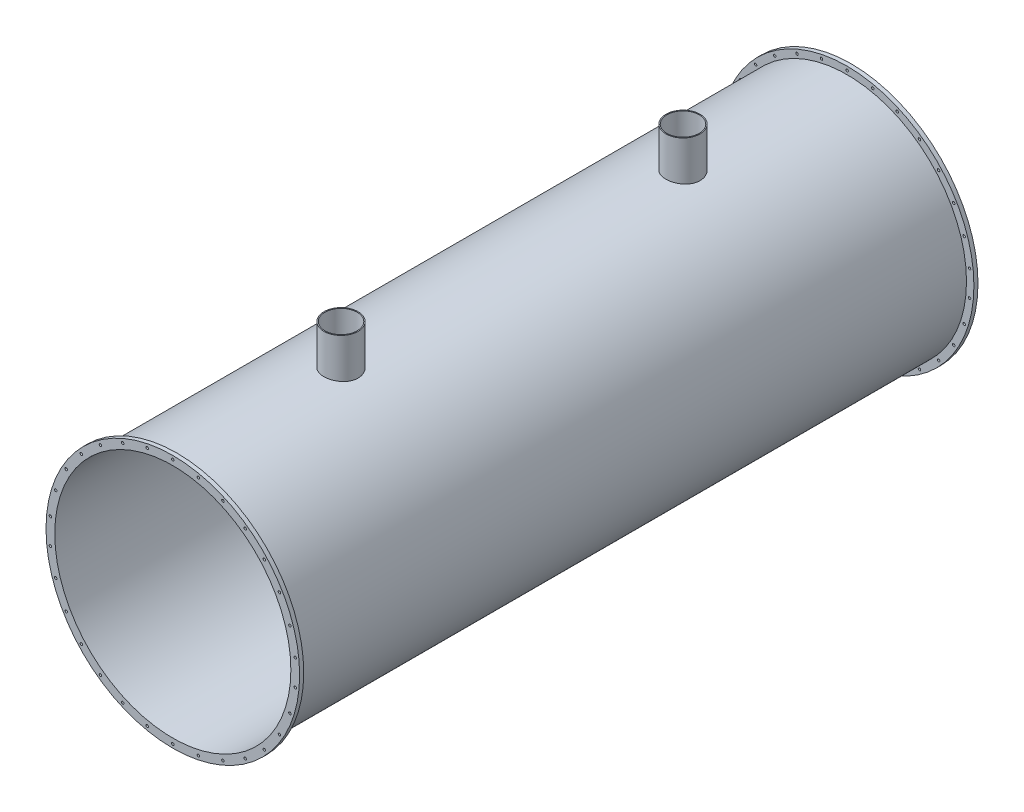
SolidWorks part; units mm, degrees
ref_plane "Front Plane" through (0, 0, 0) normal (0, 0, 1) x (1, 0, 0)
ref_plane "Top Plane" through (0, 0, 0) normal (0, 1, 0) x (1, 0, 0)
ref_plane "Right Plane" through (0, 0, 0) normal (1, 0, 0) x (0, 0, -1)
sketch "Sketch1" plane through (0, 0, 0) normal (0, 0, 1) x (1, 0, 0)
  circle A0 centre (0, 0) radius 2105.5785
  circle A1 centre (0, 0) radius 2130.0235
  dimension "D1" = 4211.157
  dimension "D2" = 4260.047
extrude "Boss-Extrude1" add sketch "Sketch1" against normal blind 12100
sketch "Sketch2" plane through (0, 0, 0) normal (0, 1, 0) x (1, 0, 0)
  circle A0 centre (0, 3000) radius 304.8
  dimension "D2" = 609.6
extrude "Cut-Extrude2" cut sketch "Sketch2" along normal blind 2300
ref_plane "Plane1" through (3000, 0, 0) normal (1, 0, 0) x (0, 0, -1)
sketch "Sketch4" plane through (0, 0, 0) normal (0, 1, 0) x (1, 0, 0)
  circle A2 centre (0, 9100) radius 304.8
extrude "Cut-Extrude3" cut sketch "Sketch4" along normal blind 5000
ref_plane "Plane2" through (0, 2830.0235, 0) normal (0, 1, 0) x (-1, 0, 0)
sketch "Sketch5" plane through (0, 2830.0235, 0) normal (0, 1, 0) x (-1, 0, 0)
  circle A0 centre (0, -3000) radius 304.8
  circle A1 centre (0, -9100) radius 304.8
extrude "Boss-Extrude2" add sketch "Sketch5" against normal blind 760
sketch "Sketch6" plane through (0, 2830.0235, 0) normal (0, 1, 0) x (-1, 0, 0)
  circle A0 centre (0, -3000) radius 287.4
  circle A1 centre (0, -9100) radius 287.4
  dimension "D1" = 574.8
  dimension "D2" = 574.8
extrude "Cut-Extrude4" cut sketch "Sketch6" against normal blind 760
sketch "Sketch7" plane through (0, 0, 0) normal (0, 0, 1) x (1, 0, 0)
  circle A0 centre (0, 0) radius 2105.5785
extrude "Cut-Extrude5" cut sketch "Sketch7" against normal through all
sketch "Sketch8" plane through (0, 0, 0) normal (0, 0, 1) x (1, 0, 0)
  circle A0 centre (0, 0) radius 2262.0235
  circle A1 centre (0, 0) radius 2130.0235
extrude "Boss-Extrude3" add sketch "Sketch8" against normal blind 73
sketch "Sketch9" plane through (0, 0, 0) normal (0, 0, 1) x (1, 0, 0)
  line L0 (0, 0) -> (0, 2196.0235) construction
  line L1 (0, 0) -> (456.579, 2148.0351) construction
  circle A1 centre (0, 2196.0235) radius 22
  circle A2 centre (456.579, 2148.0351) radius 22
  circle A3 centre (893.2032, 2006.1673) radius 22
  circle A4 centre (1290.7902, 1776.6203) radius 22
  circle A5 centre (1631.9635, 1469.4265) radius 22
  circle A6 centre (1901.8121, 1098.0117) radius 22
  circle A7 centre (2088.5425, 678.6086) radius 22
  circle A8 centre (2183.9935, 229.547) radius 22
  circle A9 centre (2183.9935, -229.547) radius 22
  circle A10 centre (2088.5425, -678.6086) radius 22
  circle A11 centre (1901.8121, -1098.0118) radius 22
  circle A12 centre (1631.9635, -1469.4265) radius 22
  circle A13 centre (1290.7902, -1776.6203) radius 22
  circle A14 centre (893.2032, -2006.1673) radius 22
  circle A15 centre (456.579, -2148.0351) radius 22
  circle A16 centre (0, -2196.0235) radius 22
  circle A17 centre (-456.579, -2148.0351) radius 22
  circle A18 centre (-893.2032, -2006.1673) radius 22
  circle A19 centre (-1290.7902, -1776.6203) radius 22
  circle A20 centre (-1631.9635, -1469.4265) radius 22
  circle A21 centre (-1901.8121, -1098.0117) radius 22
  circle A22 centre (-2088.5425, -678.6086) radius 22
  circle A23 centre (-2183.9935, -229.547) radius 22
  circle A24 centre (-2183.9935, 229.547) radius 22
  circle A25 centre (-2088.5425, 678.6086) radius 22
  circle A26 centre (-1901.8121, 1098.0118) radius 22
  circle A27 centre (-1631.9635, 1469.4265) radius 22
  circle A28 centre (-1290.7902, 1776.6203) radius 22
  circle A29 centre (-893.2032, 2006.1673) radius 22
  circle A30 centre (-456.579, 2148.0351) radius 22
  dimension "D2" = 44
  dimension "D1" = 30
  dimension "D3" = 12
extrude "Cut-Extrude6" cut sketch "Sketch9" against normal blind 100
ref_plane "Plane3" through (0, 0, -12100) normal (0, 0, -1) x (-1, 0, 0)
sketch "Sketch11" plane through (0, 0, -12100) normal (0, 0, -1) x (-1, 0, 0)
  circle A0 centre (0, 0) radius 2262.0235
  circle A1 centre (0, 0) radius 2130.0235
extrude "Boss-Extrude4" add sketch "Sketch11" against normal blind 73
sketch "Sketch12" plane through (0, 0, -12100) normal (0, 0, -1) x (-1, 0, 0)
  line L0 (0, 0) -> (0, 2196.0235) construction
  line L1 (0, 0) -> (456.579, 2148.0351) construction
  circle A1 centre (0, 2196.0235) radius 22
  circle A2 centre (456.579, 2148.0351) radius 22
  circle A3 centre (893.2032, 2006.1673) radius 22
  circle A4 centre (1290.7902, 1776.6203) radius 22
  circle A5 centre (1631.9635, 1469.4265) radius 22
  circle A6 centre (1901.8121, 1098.0117) radius 22
  circle A7 centre (2088.5425, 678.6086) radius 22
  circle A8 centre (2183.9935, 229.547) radius 22
  circle A9 centre (2183.9935, -229.547) radius 22
  circle A10 centre (2088.5425, -678.6086) radius 22
  circle A11 centre (1901.8121, -1098.0118) radius 22
  circle A12 centre (1631.9635, -1469.4265) radius 22
  circle A13 centre (1290.7902, -1776.6203) radius 22
  circle A14 centre (893.2032, -2006.1673) radius 22
  circle A15 centre (456.579, -2148.0351) radius 22
  circle A16 centre (0, -2196.0235) radius 22
  circle A17 centre (-456.579, -2148.0351) radius 22
  circle A18 centre (-893.2032, -2006.1673) radius 22
  circle A19 centre (-1290.7902, -1776.6203) radius 22
  circle A20 centre (-1631.9635, -1469.4265) radius 22
  circle A21 centre (-1901.8121, -1098.0117) radius 22
  circle A22 centre (-2088.5425, -678.6086) radius 22
  circle A23 centre (-2183.9935, -229.547) radius 22
  circle A24 centre (-2183.9935, 229.547) radius 22
  circle A25 centre (-2088.5425, 678.6086) radius 22
  circle A26 centre (-1901.8121, 1098.0118) radius 22
  circle A27 centre (-1631.9635, 1469.4265) radius 22
  circle A28 centre (-1290.7902, 1776.6203) radius 22
  circle A29 centre (-893.2032, 2006.1673) radius 22
  circle A30 centre (-456.579, 2148.0351) radius 22
  dimension "D2" = 44
  dimension "D1" = 30
  dimension "D3" = 12
  dimension "D4" = 2196.0235
extrude "Cut-Extrude7" cut sketch "Sketch12" against normal blind 1000
sketch "Sketch13" plane through (0, 0, -12100) normal (0, 0, -1) x (-1, 0, 0)
sketch "Sketch14" plane through (0, 0, -12100) normal (0, 0, -1) x (-1, 0, 0)
sketch "Sketch15" plane through (0, 0, -12100) normal (0, 0, -1) x (-1, 0, 0)
